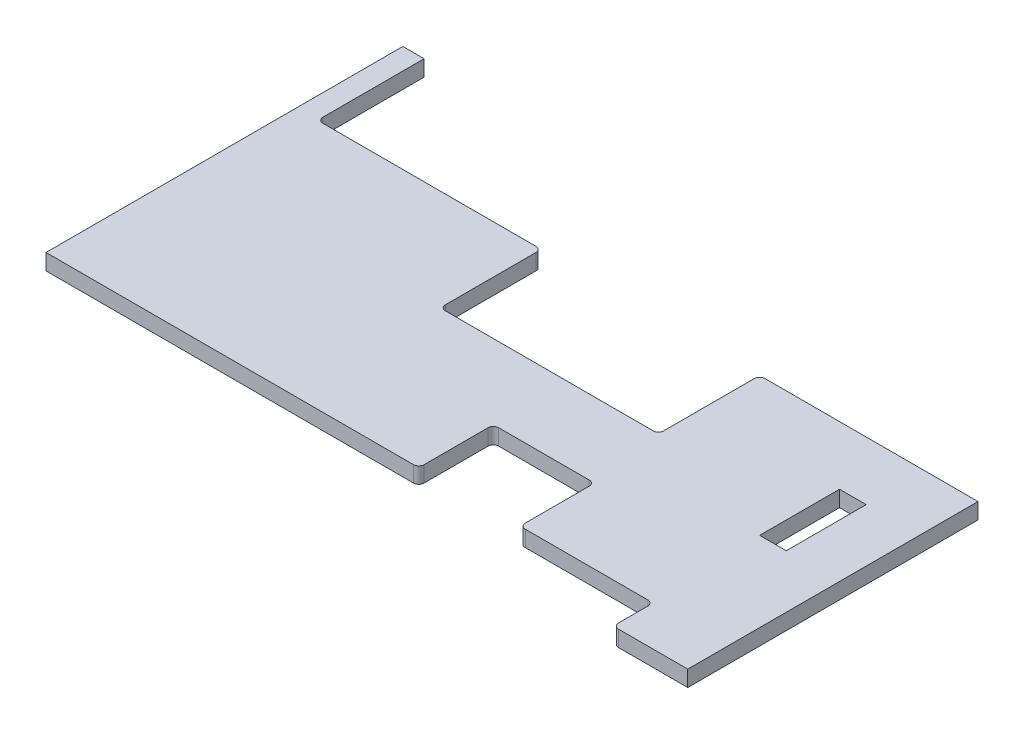
SolidWorks part; units mm, degrees
ref_plane "Front Plane" through (0, 0, 0) normal (0, 0, 1) x (1, 0, 0)
ref_plane "Top Plane" through (0, 0, 0) normal (0, 1, 0) x (1, 0, 0)
ref_plane "Right Plane" through (0, 0, 0) normal (1, 0, 0) x (0, 0, -1)
sketch "Sketch1" plane through (0, 0, 0) normal (0, 1, 0) x (1, 0, 0)
  line L26 (0, 67) -> (4, 67)
  line L27 (4, 67) -> (4, 47)
  line L28 (4, 47) -> (46, 47)
  line L29 (46, 47) -> (46, 28)
  line L30 (46, 28) -> (87, 28)
  line L31 (87, 28) -> (87, 47)
  line L32 (87, 47) -> (128, 47)
  line L33 (128, 47) -> (128, -7.5)
  line L34 (128, -7.5) -> (114, -7.5)
  line L35 (114, -7.5) -> (114, 0)
  line L36 (114, 0) -> (89, 0)
  line L37 (89, 0) -> (89, 14)
  line L38 (89, 14) -> (70, 14)
  line L39 (70, 14) -> (70, 0)
  line L40 (70, 0) -> (0, 0)
  line L43 (0, 67) -> (0, 0)
  dimension "D2" = 4
  dimension "D3" = 42
  dimension "D4" = 41
  dimension "D5" = 41
  dimension "D6" = 19
  dimension "D7" = 19
  dimension "D8" = 67
  dimension "D9" = 70
  dimension "D10" = 19
  dimension "D11" = 25
  dimension "D12" = 14
  dimension "D13" = 20
  dimension "D15" = 7.5
extrude "Boss-Extrude1" add sketch "Sketch1" along normal blind 3
sketch "Sketch2" plane through (0, 3, 0) normal (0, 1, 0) x (1, 0, 0)
  line L0 (128, -7.5) -> (128, 47) construction
  line L1 (113, 36) -> (118, 36)
  line L2 (113, 36) -> (113, 21)
  line L3 (113, 21) -> (118, 21)
  line L4 (118, 36) -> (118, 21)
  line L5 (128, 47) -> (87, 47) construction
  dimension "D1" = 5
  dimension "D2" = 15
  dimension "D3" = 10
  dimension "D4" = 11
extrude "Cut-Extrude1" cut sketch "Sketch2" against normal through all
fillet "Fillet1" radius 1 11 edges at (114, 1.5, 7.5) (114, 1.5, 0) (89, 1.5, 0) (70, 1.5, 0) (89, 1.5, -14) (70, 1.5, -14) (87, 1.5, -47) (87, 1.5, -28) (46, 1.5, -28) (46, 1.5, -47) (4, 1.5, -47)
